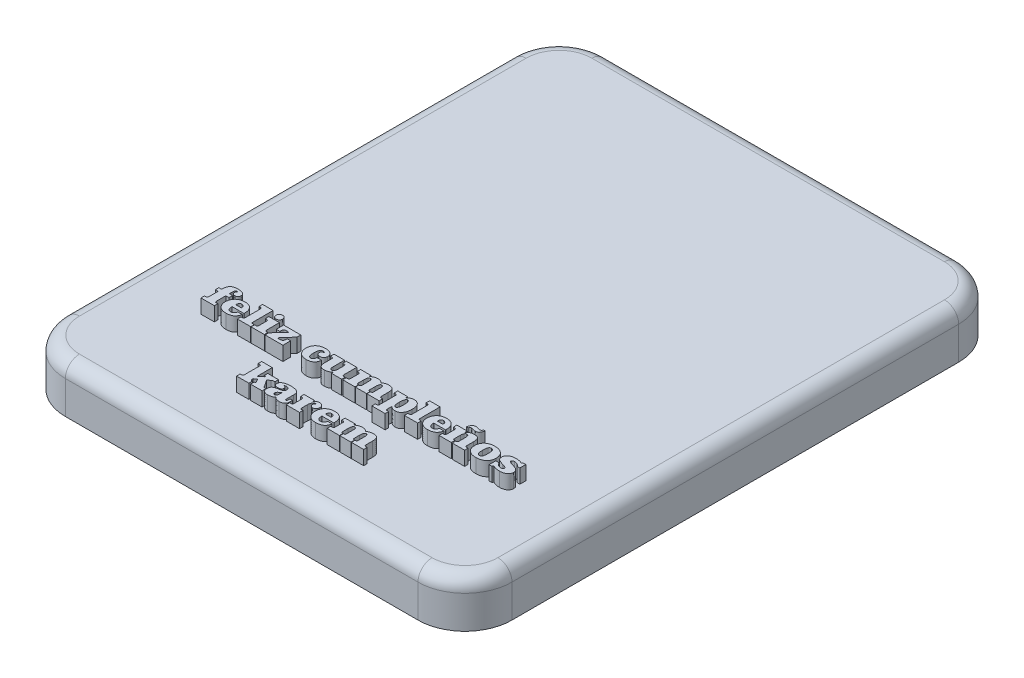
SolidWorks part; units mm, degrees
ref_plane "Alzado" through (0, 0, 0) normal (0, 0, 1) x (1, 0, 0)
ref_plane "Planta" through (0, 0, 0) normal (0, 1, 0) x (1, 0, 0)
ref_plane "Vista lateral" through (0, 0, 0) normal (1, 0, 0) x (0, 0, -1)
sketch "Croquis1" plane through (0, 0, 0) normal (0, 1, 0) x (1, 0, 0)
  line L1 (-37.5, -57.5) -> (37.5, -57.5)
  line L2 (-47.5, -47.5) -> (-47.5, 47.5)
  line L3 (-37.5, 57.5) -> (37.5, 57.5)
  line L4 (47.5, -47.5) -> (47.5, 47.5)
  line L5 (-47.5, -57.5) -> (47.5, 57.5) construction
  line L6 (-47.5, 57.5) -> (47.5, -57.5) construction
  arc A0 (-37.5, -57.5) -> (-47.5, -47.5) centre (-37.5, -47.5) cw
  arc A1 (37.5, -57.5) -> (47.5, -47.5) centre (37.5, -47.5) ccw
  arc A2 (37.5, 57.5) -> (47.5, 47.5) centre (37.5, 47.5) cw
  arc A3 (-47.5, 47.5) -> (-37.5, 57.5) centre (-37.5, 47.5) cw
  point P0 (0, 0)
  dimension "D3" = 10
  dimension "D1" = 95
  dimension "D2" = 115
extrude "Saliente-Extruir1" add sketch "Croquis1" along normal blind 10
fillet "Redondeo1" radius 3 8 edges at (-44.5711, 10, 54.5711) (-47.5, 10, 0) (-44.5711, 10, -54.5711) (0, 10, -57.5) (44.5711, 10, -54.5711) (47.5, 10, 0) (44.5711, 10, 54.5711) (0, 10, 57.5)
sketch "Croquis2" plane through (0, 10, 0) normal (0, 1, 0) x (1, 0, 0)
  text T0 "feliz cumpleños\r\n       karem" font "Clarendon Blk BT" height in points 20
extrude "Saliente-Extruir3" add sketch "Croquis2" along normal blind 3
